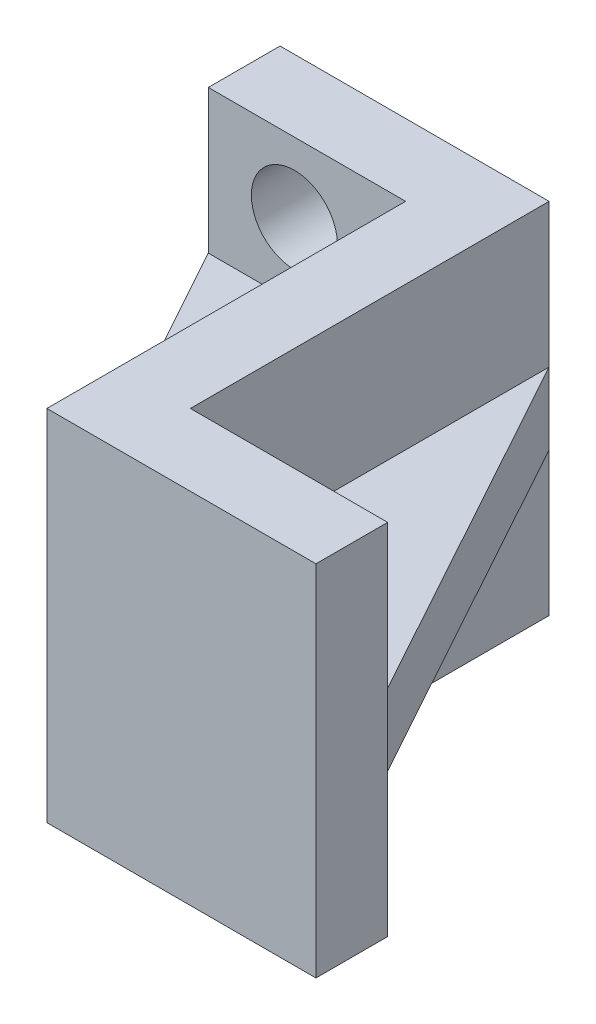
SolidWorks part; units mm, degrees
ref_plane "Front Plane" through (0, 0, 0) normal (1, 0, 0) x (0, 1, 0)
ref_plane "Top Plane" through (0, 0, 0) normal (0, 0, 1) x (0, 1, 0)
ref_plane "Right Plane" through (0, 0, 0) normal (0, 1, 0) x (-1, 0, 0)
sketch "Sketch1" plane through (0, 0, 0) normal (1, 0, 0) x (0, 1, 0)
  line L1 (-100, 120) -> (100, 120)
  line L2 (-100, 120) -> (-100, -120)
  line L3 (-100, -120) -> (100, -120)
  line L4 (100, 120) -> (100, -120)
  line L5 (-100, 120) -> (100, -120) construction
  line L6 (-100, -120) -> (100, 120) construction
  point P0 (0, 0)
  dimension "D1" = 240
  dimension "D2" = 200
extrude "Boss-Extrude1" add sketch "Sketch1" along normal mid plane 40
sketch "Sketch2" plane through (20, 0, 0) normal (1, 0, 0) x (0, 1, 0)
  line L0 (100, -120) -> (100, 120) construction
  line L1 (-100, 120) -> (100, 120)
  line L2 (-100, 120) -> (-100, 80)
  line L3 (-100, 80) -> (100, 80)
  line L4 (100, 120) -> (100, 80)
  dimension "D1" = 40
extrude "Boss-Extrude2" add sketch "Sketch2" along normal blind 110
sketch "Sketch3" plane through (-20, 0, 0) normal (-1, 0, 0) x (0, -1, 0)
  line L0 (100, 120) -> (100, -120) construction
  line L1 (-100, -120) -> (100, -120)
  line L2 (-100, -120) -> (-100, -80)
  line L3 (-100, -80) -> (100, -80)
  line L4 (100, -120) -> (100, -80)
  dimension "D1" = 40
extrude "Boss-Extrude3" add sketch "Sketch3" along normal blind 110
sketch "Sketch4" plane through (0, 0, 0) normal (0, 1, 0) x (-1, 0, 0)
  line L0 (-130, 80) -> (-20, -120)
rib "Rib1" sketch "Sketch4" sketch "Sketch4" thickness 40 extrusion direction parallel to sketch draft on no parameters "D1"=40
sketch "Sketch6" plane through (0, 0, 0) normal (0, 1, 0) x (-1, 0, 0)
  line L0 (20, 120) -> (130, -80)
rib "Rib2" sketch "Sketch6" sketch "Sketch6" thickness 40 extrusion direction parallel to sketch draft on no parameters "D1"=40
sketch "Sketch7" plane through (0, 0, -80) normal (0, 0, 1) x (1, 0, 0)
  line L0 (-130, -100) -> (-130, -20) construction
  line L1 (-130, -20) -> (-20, -20) construction
  line L2 (0, 0) -> (-51.6344, 0) construction
  circle A0 centre (-82, -60) radius 24
  circle A1 centre (-82, 60) radius 24
  point P4 (-130, -60)
  dimension "D1" = 48
  dimension "D2" = 48
  dimension "D3" = 40
extrude "Cut-Extrude1" cut sketch "Sketch7" against normal through all both and the other way through all
